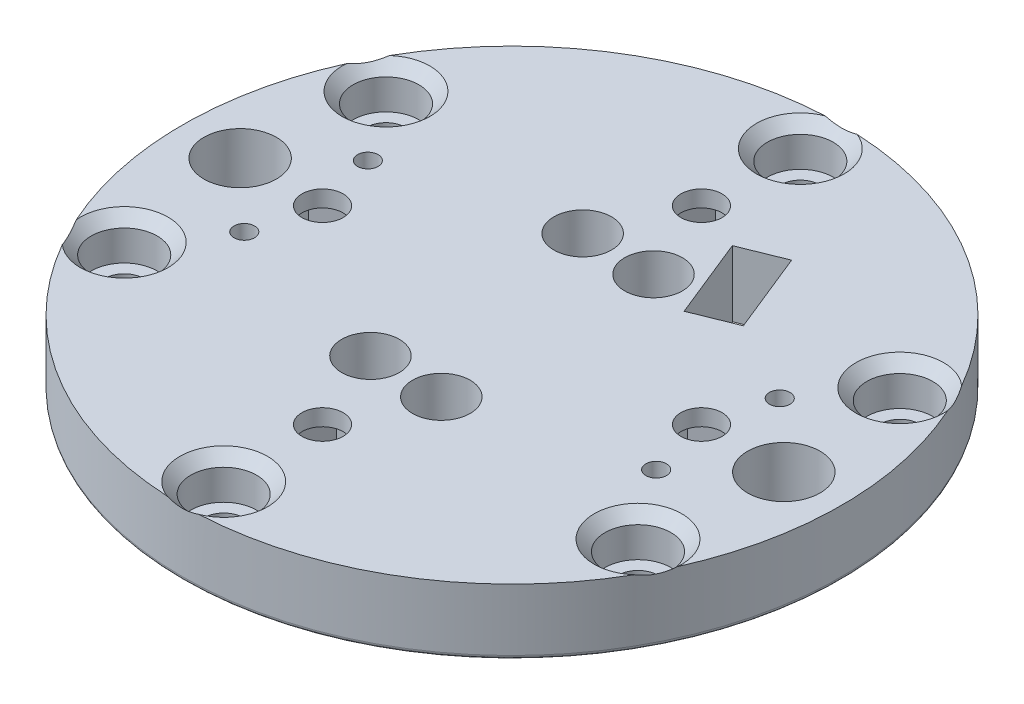
SolidWorks part; units mm, degrees
material "ABS"
ref_plane "Front Plane" through (0, 0, 0) normal (0, 0, 1) x (1, 0, 0)
ref_plane "Top Plane" through (0, 0, 0) normal (0, 1, 0) x (1, 0, 0)
ref_plane "Right Plane" through (0, 0, 0) normal (1, 0, 0) x (0, 0, -1)
sketch "Sketch1" plane through (0, 0, 0) normal (0, 0, 1) x (1, 0, 0)
  line L0 (40, 8) -> (0, 8)
  line L1 (0, 8) -> (0, 0)
  line L2 (0, 0) -> (40, 0)
  line L3 (40, 0) -> (40, 8)
  line L4 (0, 8) -> (0, 0) construction
revolve "Revolve1" add sketch "Sketch1" angle 360 about L4
sketch "Sketch2" plane through (0, 8, 0) normal (0, 1, 0) x (-1, 0, 0)
  line L0 (-6.0697, -20.6796) -> (-10.0405, -10.8514)
  line L1 (-10.0405, -10.8514) -> (-15.1638, -12.9213)
  line L2 (-15.1638, -12.9213) -> (-11.1929, -22.7495)
  line L3 (-11.1929, -22.7495) -> (-6.0697, -20.6796)
extrude "Cut-Extrude1" cut sketch "Sketch2" against normal through all
sketch "Sketch3" plane through (0, 0, 0) normal (0, -1, 0) x (1, 0, 0)
  line L0 (6.5, -1) -> (-6.5, -1)
  line L1 (-6.5, -1) -> (-6.5, 1)
  line L2 (-6.5, 1) -> (6.5, 1)
  line L3 (6.5, 1) -> (6.5, -1)
extrude "Boss-Extrude1" add sketch "Sketch3" along normal blind 3.5
sketch "Sketch4" plane through (0, 0, 0) normal (0, -1, 0) x (1, 0, 0)
  line L0 (-2.295, 26.975) -> (-4.5899, 23)
  line L1 (-4.5899, 23) -> (-2.295, 19.025)
  line L2 (-2.295, 19.025) -> (2.295, 19.025)
  line L3 (2.295, 19.025) -> (4.5899, 23)
  line L4 (4.5899, 23) -> (2.295, 26.975)
  line L5 (2.295, 26.975) -> (-2.295, 26.975)
extrude "Cut-Extrude2" cut sketch "Sketch4" against normal blind 6
sketch "Sketch5" plane through (0, 0, 0) normal (0, -1, 0) x (1, 0, 0)
  line L0 (-26.975, -2.295) -> (-23, -4.5899)
  line L1 (-23, -4.5899) -> (-19.025, -2.295)
  line L2 (-19.025, -2.295) -> (-19.025, 2.295)
  line L3 (-19.025, 2.295) -> (-23, 4.5899)
  line L4 (-23, 4.5899) -> (-26.975, 2.295)
  line L5 (-26.975, 2.295) -> (-26.975, -2.295)
extrude "Cut-Extrude3" cut sketch "Sketch5" against normal blind 6
sketch "Sketch6" plane through (0, 0, 0) normal (0, -1, 0) x (1, 0, 0)
  line L0 (2.295, -26.975) -> (4.5899, -23)
  line L1 (4.5899, -23) -> (2.295, -19.025)
  line L2 (2.295, -19.025) -> (-2.295, -19.025)
  line L3 (-2.295, -19.025) -> (-4.5899, -23)
  line L4 (-4.5899, -23) -> (-2.295, -26.975)
  line L5 (-2.295, -26.975) -> (2.295, -26.975)
extrude "Cut-Extrude4" cut sketch "Sketch6" against normal blind 6
sketch "Sketch7" plane through (0, 0, 0) normal (0, -1, 0) x (1, 0, 0)
  line L0 (26.975, 2.295) -> (23, 4.5899)
  line L1 (23, 4.5899) -> (19.025, 2.295)
  line L2 (19.025, 2.295) -> (19.025, -2.295)
  line L3 (19.025, -2.295) -> (23, -4.5899)
  line L4 (23, -4.5899) -> (26.975, -2.295)
  line L5 (26.975, -2.295) -> (26.975, 2.295)
extrude "Cut-Extrude5" cut sketch "Sketch7" against normal blind 6
hole_wizard "Ø7.0 (7) Diameter Hole1" positions "Sketch9" profile "Sketch8" hole size "Ø7.0" standard "ANSI Metric"
sketch "Sketch9" plane through (0, 0, 0) normal (0, -1, 0) x (-1, 0, 0)
  point P0 (4.3, -12.88)
  point P1 (4.3, 12.88)
  point P2 (-4.3, 12.88)
  point P3 (-4.3, -12.88)
sketch "Sketch8" plane through (-4.3, 0, 12.88) normal (1, 0, 0) x (0, 0, -1)
  line L0 (0, 0) -> (0, 8)
  line L1 (0, 8) -> (3.5, 8)
  line L2 (3.5, 8) -> (3.5, 0)
  line L5 (3.5, 0) -> (0, 0)
  line L11 (0, -6.35) -> (0, 107.95) construction
  dimension "Thru Hole Dia." = 7
  dimension "Thru Hole Depth" = 8
hole_wizard "Ø2.5 (2.5) Diameter Hole1" positions "Sketch11" profile "Sketch10" hole size "Ø2.5" standard "ANSI Metric"
sketch "Sketch11" plane through (0, 8, 0) normal (0, 1, 0) x (1, 0, 0)
  point P0 (25, -7.5)
  point P1 (25, 7.5)
  point P2 (-25, 7.5)
  point P3 (-25, -7.5)
sketch "Sketch10" plane through (25, 8, 7.5) normal (1, 0, 0) x (0, 0, 1)
  line L0 (0, 0) -> (0, 11.5)
  line L1 (0, 11.5) -> (1.25, 11.5)
  line L2 (1.25, 11.5) -> (1.25, 0)
  line L5 (1.25, 0) -> (0, 0)
  line L11 (0, -6.35) -> (0, 107.95) construction
  dimension "Thru Hole Dia." = 2.5
  dimension "Thru Hole Depth" = 11.5
hole_wizard "Ø8.8 (8.8) Diameter Hole1" positions "Sketch13" profile "Sketch12" hole size "Ø8.8" standard "ANSI Metric"
sketch "Sketch13" plane through (0, 8, 0) normal (0, 1, 0) x (1, 0, 0)
  point P0 (33, 0)
  point P1 (-33, 0)
sketch "Sketch12" plane through (33, 8, 0) normal (1, 0, 0) x (0, 0, 1)
  line L0 (0, 0) -> (0, 11.5)
  line L1 (0, 11.5) -> (4.4, 11.5)
  line L2 (4.4, 11.5) -> (4.4, 0)
  line L5 (4.4, 0) -> (0, 0)
  line L11 (0, -6.35) -> (0, 107.95) construction
  dimension "Thru Hole Dia." = 8.8
  dimension "Thru Hole Depth" = 11.5
hole_wizard "CBORE for M4 Hex Head Machine Screw1" positions "Sketch15" profile "Sketch14" counterbore size "M4" standard "ANSI Metric"
sketch "Sketch15" plane through (0, 8, 0) normal (0, 1, 0) x (1, 0, 0)
  point P0 (-31.1852, -15.8897)
  point P1 (0, -35)
  point P2 (31.1852, -15.8897)
  point P3 (-31.1852, 15.8897)
  point P4 (0, 35)
  point P5 (31.1852, 15.8897)
sketch "Sketch14" plane through (-31.1852, 8, 15.8897) normal (1, 0, 0) x (0, 0, 1)
  line L0 (0, 0) -> (0, 11.5)
  line L1 (0, 11.5) -> (2.4, 11.5)
  line L3 (2.4, 11.5) -> (2.4, 5)
  line L4 (4, 5) -> (2.4, 5)
  line L5 (4, 5) -> (4, 1.32)
  line L6 (4, 1.32) -> (5.32, 0)
  line L7 (5.32, 0) -> (0, 0)
  line L8 (-4, 1.32) -> (-5.32, 0) construction
  line L11 (0, -6.35) -> (0, 107.95) construction
  dimension "Thru Hole Dia." = 4.8
  dimension "Thru Hole Depth" = 11.5
  dimension "C'Bore Dia." = 8
  dimension "C'Bore Depth" = 5
  dimension "Near C'Sink Dia." = 10.64
  dimension "Near C'Sink Angle" = 90
hole_wizard "Ø5.0 (5) Diameter Hole1" positions "Sketch17" profile "Sketch16" hole size "Ø5.0" standard "ANSI Metric"
sketch "Sketch17" plane through (0, 6, 0) normal (0, -1, 0) x (-1, 0, 0)
  point P0 (-23, 0)
  point P1 (0, 23)
  point P2 (23, 0)
  point P3 (0, -23)
sketch "Sketch16" plane through (23, 6, 0) normal (1, 0, 0) x (0, 0, -1)
  line L0 (0, 0) -> (0, 2)
  line L1 (0, 2) -> (2.5, 2)
  line L2 (2.5, 2) -> (2.5, 0)
  line L5 (2.5, 0) -> (0, 0)
  line L11 (0, -6.35) -> (0, 107.95) construction
  dimension "Thru Hole Dia." = 5
  dimension "Thru Hole Depth" = 2
fillet "Fillet1" radius 0.5 1 edges at (0, 0, -40)
